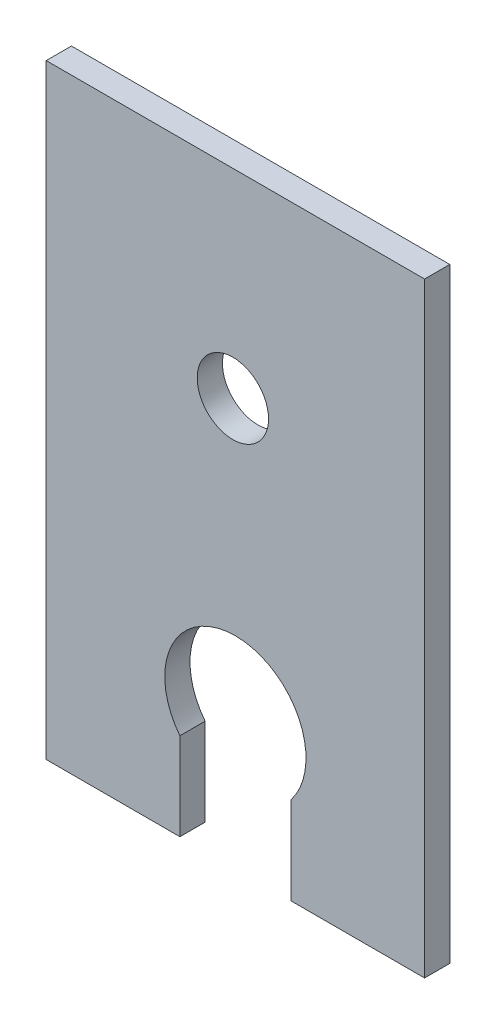
SolidWorks part; units mm, degrees
material "PW100:Mi:0:7:C1:0:1:2:Re:26:"
ref_plane "Plan1" through (0, 0, 0) normal (0, 0, 1) x (1, 0, 0)
ref_plane "Plan2" through (0, 0, 0) normal (0, 1, 0) x (1, 0, 0)
ref_plane "Plan3" through (0, 0, 0) normal (1, 0, 0) x (0, 0, -1)
sketch "Esquisse1" plane through (0, 0, 0) normal (0, 0, 1) x (1, 0, 0)
  line L1 (0, 0) -> (150, 0)
  line L2 (0, 0) -> (0, 240)
  line L3 (0, 240) -> (150, 240)
  line L4 (150, 0) -> (150, 240)
extrude "Base-Extrusion" add sketch "Esquisse1" along normal blind 10
sketch "Esquisse2" plane through (0, 0, 10) normal (0, 0, 1) x (1, 0, 0)
  line L0 (0, 0) -> (150, 0) construction
  line L1 (53, 0) -> (97, 0)
  line L2 (53, 0) -> (53, 34.6795)
  line L4 (97, 0) -> (97, 34.6795)
  arc A0 (97, 34.6795) -> (53, 34.6795) centre (75, 52) ccw
extrude "Enlèv. mat.-Extru.1" cut sketch "Esquisse2" against normal blind 10
sketch "Esquisse3" plane through (0, 0, 10) normal (0, 0, 1) x (1, 0, 0)
  circle A0 centre (74, 161) radius 14.1421
extrude "Enlèv. mat.-Extru.2" cut sketch "Esquisse3" against normal blind 10
